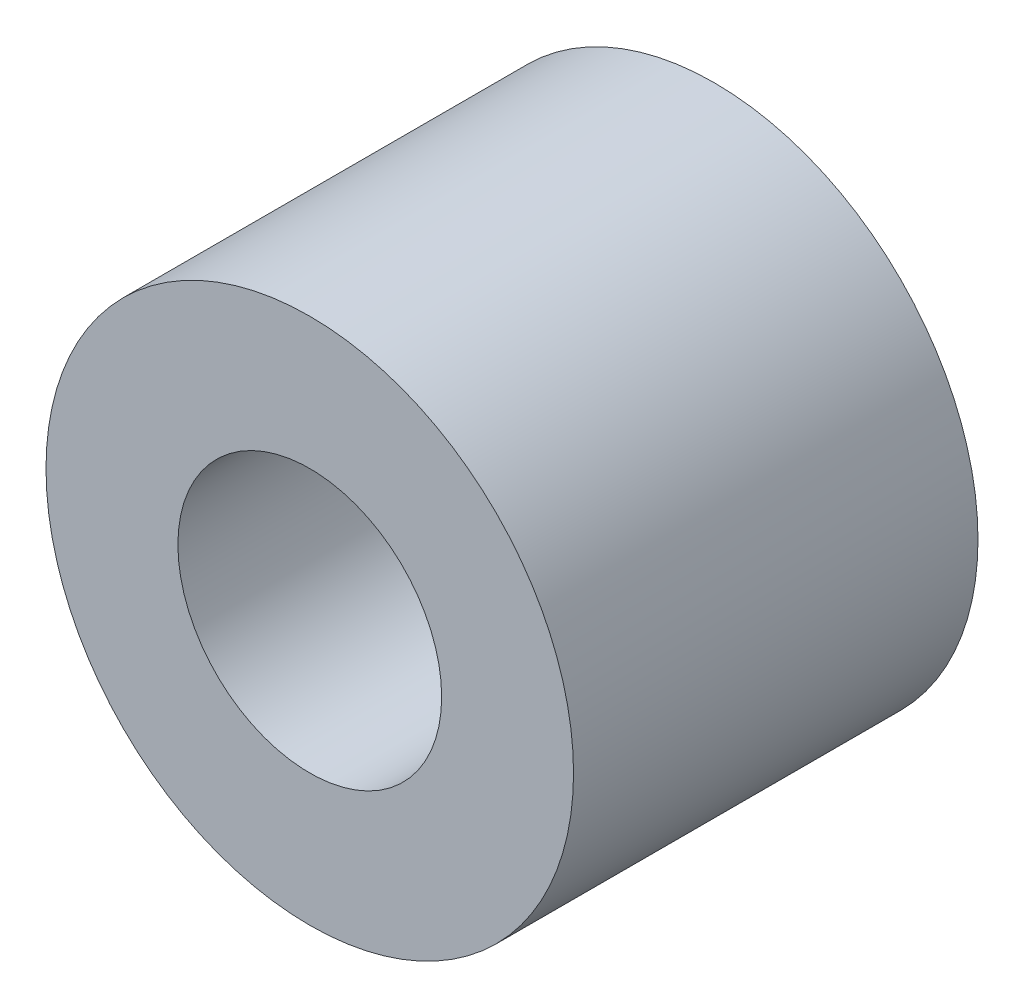
SolidWorks part; units mm, degrees
ref_plane "前视基准面" through (0, 0, 0) normal (0, 0, 1) x (1, 0, 0)
ref_plane "上视基准面" through (0, 0, 0) normal (0, 1, 0) x (1, 0, 0)
ref_plane "右视基准面" through (0, 0, 0) normal (1, 0, 0) x (0, 0, -1)
sketch "草图1" plane through (0, 0, 0) normal (0, 0, 1) x (1, 0, 0)
  circle A0 centre (0, 0) radius 4.5
  circle A1 centre (0, 0) radius 2.25
  dimension "D1" = 4.5
  dimension "D2" = 9
extrude "凸台-拉伸1" add sketch "草图1" along normal blind 6.9
